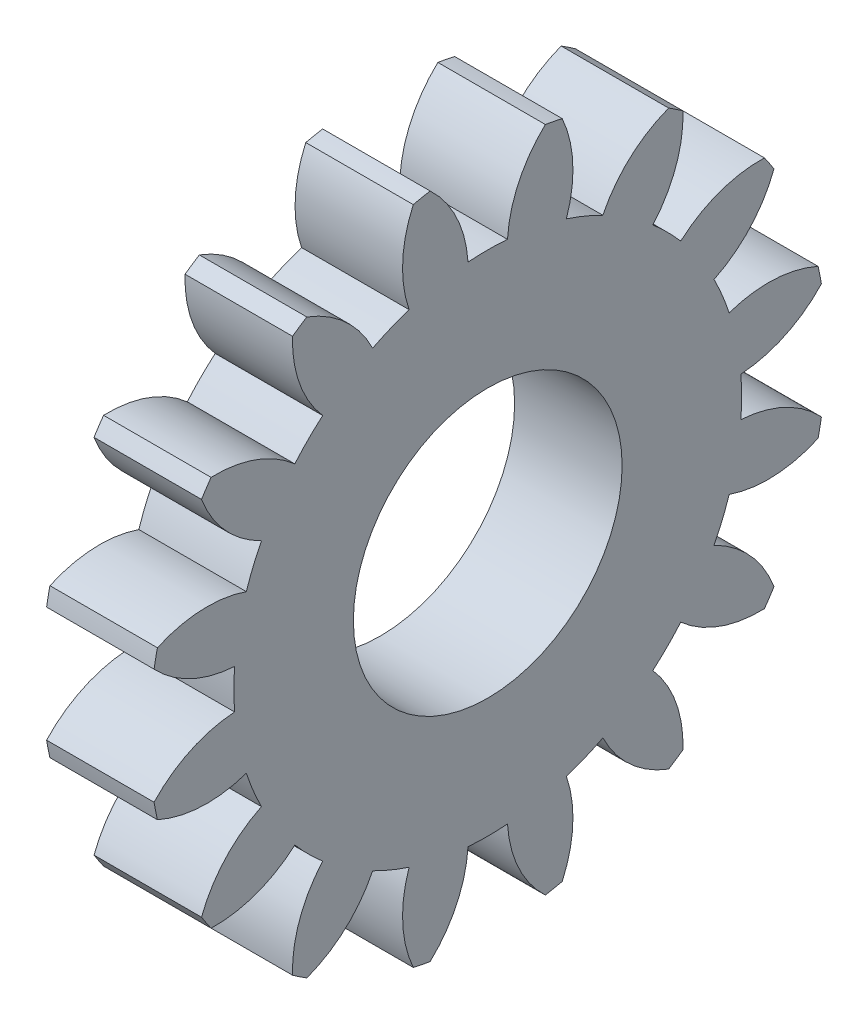
SolidWorks part; units mm, degrees
ref_plane "Plane1" through (0, 0, 0) normal (0, 0, 1) x (1, 0, 0)
ref_plane "Plane2" through (0, 0, 0) normal (0, 1, 0) x (1, 0, 0)
ref_plane "Plane3" through (0, 0, 0) normal (1, 0, 0) x (0, 0, -1)
sketch "HoldingSke" plane through (0, 0, 0) normal (0, 1, 0) x (1, 0, 0)
  line L0 (0, 0) -> (1.3732, -0.3938)
  line L1 (-15, 0) -> (100, 0) construction
  line L2 (0, 0) -> (-2.1039, 2.3779)
  line L3 (0, 0) -> (-11.863, 4.5341)
  line L4 (0, 0) -> (8.3015, 2.3804)
  line L5 (0, 0) -> (-46.8476, -17.4728)
  line L6 (0, 0) -> (-1.6579, -1.1186)
  line L7 (-2.1039, 2.3779) -> (8.6586, 51.2059)
  line L8 (-76.2, 54.61) -> (-75.3, 54.61)
  line L9 (-71.009, 38.7566) -> (-53.1078, 45.2721)
  line L10 (-76.2, 71.12) -> (104.1128, 71.12)
  line L11 (0, 0) -> (-2, 0)
  line L12 (-76.2, 101.6) -> (-76.173, 101.6)
  line L13 (24.9733, 27.94) -> (52.9518, 28.4284)
  line L14 (24.9733, 27.94) -> (24.9743, 27.94)
  line L15 (24.9733, 27.94) -> (100.4006, 29.5858)
  line L16 (-63.627, -0.7) -> (-12.827, -0.7)
  circle A0 centre (0, 0) radius 2.5
  circle A1 centre (0, 0) radius 4.724
  circle A2 centre (0, 0) radius 37.5
  circle A3 centre (0, 0) radius 2.5
  dimension "Hub_dia" = 75
  dimension "Overall_len" = 50
  dimension "OAL" = 50.0001
  dimension "Ap" = 20
  dimension "H" = 19.05
  dimension "Pitch_radius" = 180.3128
  dimension "Addendum_fac" = 1
  dimension "Dedendum_fac" = 1.25
  dimension "Clearance_fac" = 0.25
  dimension "Dedendum_add" = 0.001
sketch "BasProSke" plane through (0, 0, 0) normal (0, 1, 0) x (1, 0, 0)
  line L0 (-10, 0) -> (60, 0) construction
  line L1 (0, 0) -> (0, 6.3)
  line L2 (0, 0) -> (2, 0)
  line L3 (2, 0) -> (2, 6.3)
  line L4 (2, 6.3) -> (0, 6.3)
revolve "Base-Revolve" add sketch "BasProSke" angle 360 about L0
sketch "TooCutSke" plane through (0, 0, 0) normal (1, 0, 0) x (0, 0, -1)
  line L1 (0, 0) -> (0, 107) construction
  line L2 (0, 0) -> (-0.5961, 5.5682) construction
  line L3 (0, 0) -> (-2.1762, 10.9406) construction
  line L4 (-0.5961, 5.5682) -> (-1.0881, 5.4703) construction
  arc A0 (0.3672, 4.7097) -> (-0.3672, 4.7097) centre (0, 0) ccw
  arc A1 (1.0952, 6.2299) -> (-1.0952, 6.2299) centre (0, 0) ccw
  circle A2 centre (0, 0) radius 5.6 construction
  circle A3 centre (0, 0) radius 5.2623 construction
  arc A4 (-0.3672, 4.7097) -> (-1.0952, 6.2299) centre (-2.6031, 4.5734) ccw
  arc A5 (1.0952, 6.2299) -> (0.3672, 4.7097) centre (2.6031, 4.5734) ccw
extrude "ToothCut" cut sketch "TooCutSke" along normal through all
fillet "Breaks" [suppressed] radius 0.014
fillet "RootFillets" [suppressed] radius 0.176
pattern_circular "TeethCuts" count 16 every 22.5 about axis through (-10, 0, 0) along (1, 0, 0) of "ToothCut", "RootFillets", "Breaks"
sketch "HubNeaOneSke" plane through (0, 0, 0) normal (-1, 0, 0) x (0, 0, 1)
  circle A0 centre (0, 0) radius 4.724
extrude "HubNearOne" [suppressed] add sketch "HubNeaOneSke" along normal blind 48.0001
sketch "HubNeaBotSke" plane through (0, 0, 0) normal (-1, 0, 0) x (0, 0, 1)
  circle A0 centre (0, 0) radius 4.724
extrude "HubNearBoth" [suppressed] add sketch "HubNeaBotSke" along normal blind 24
ref_plane "FarPln" through (2, 0, 0) normal (1, 0, 0) x (0, 0, -1)
sketch "HubFarSke" plane through (2, 0, 0) normal (1, 0, 0) x (0, 0, -1)
  circle A0 centre (0, 0) radius 4.724
extrude "HubFar" [suppressed] add sketch "HubFarSke" along normal blind 24
sketch "BorSke" plane through (0, 0, 0) normal (1, 0, 0) x (0, 0, -1)
  circle A0 centre (0, 0) radius 2.5
extrude "Bore" cut sketch "BorSke" along normal mid plane 100.0001
sketch "KeySke" plane through (0, 0, 0) normal (1, 0, 0) x (0, 0, -1)
  line L0 (-1, 0) -> (-1, 3.4)
  line L1 (-1, 3.4) -> (1, 3.4)
  line L2 (1, 3.4) -> (1, 0)
  line L3 (0, 0) -> (0, 34) construction
  line L4 (-1, 0) -> (1, 0)
extrude "Keyway" [suppressed] cut sketch "KeySke" along normal mid plane 100.0001
pattern_circular "Keyway2" [suppressed] count 2 every 90 about axis through (-10, 0, 0) along (1, 0, 0)
equation "' \"Module@HoldingSke\" = 6.35"
equation "' \"Num_teeth@HoldingSke\" = 12"
equation "' \"Ap@HoldingSke\" =  20"
equation "' \"Ap@HoldingSke\" = 20"
equation "' \"Width@HoldingSke\" = 0.5 * 25.4"
equation "' \"Hub_dia@HoldingSke\"= 1 * 25.4"
equation "' \"Hub_dia@HoldingSke\" = 1 * 25.4"
equation "' \"Overall_len@HoldingSke\" = 1.0 * 25.4"
equation "' \"Bore@HoldingSke\" = 0.75 * 25.4"
equation "' \"T_dim@HoldingSke\" = 0.1 * 25.4"
equation "' \"Width@KeySke\" = 0.25 * 25.4"
equation "' \"Show_teeth@HoldingSke\" = 13"
equation "' \"Backlash@HoldingSke\" = 0.009 * 25.4"
equation "' \"Addendum_fac@HoldingSke\" = 1.0"
equation "' \"Dedendum_fac@HoldingSke\" = 1.25"
equation "' \"Dedendum_add@HoldingSke\" = 0.00005 * 25.4"
equation "' \"Clearance_fac@HoldingSke\" = 0.25"
equation "\"Pitch@HoldingSke\" = 1 / \"Module@HoldingSke\""
equation "\"Overcut_dia@TooCutSke\" = (\"Num_teeth@HoldingSke\" + 2 * \"Addendum_fac@HoldingSke\") / \"Pitch@HoldingSke\" + 0.002 * 25.4"
equation "\"Pitch_dia@TooCutSke\" = \"Num_teeth@HoldingSke\" / \"Pitch@HoldingSke\""
equation "\"Base_dia@TooCutSke\" = \"Num_teeth@HoldingSke\" / \"Pitch@HoldingSke\" * cos((\"Ap@HoldingSke\"  * 3.14159265 / 180))"
equation "\"Root_dia@TooCutSke\" = (\"Num_teeth@HoldingSke\" + 2) / \"Pitch@HoldingSke\" - 2 * (\"Addendum_fac@HoldingSke\" + \"Dedendum_fac@HoldingSke\") / \"Pitch@HoldingSke\" - \"Dedendum_add@HoldingSke\" * 2"
equation "\"Half_ang@TooCutSke\" = 180 / \"Num_teeth@HoldingSke\""
equation "\"Half_CT@TooCutSke\" = \"Num_teeth@HoldingSke\" / \"Pitch@HoldingSke\" * sin((3.14159265 / 2 / \"Num_teeth@HoldingSke\")) / 2 - 7 * \"Backlash@HoldingSke\" / 4"
equation "\"Flank_rad@TooCutSke\" = \"Num_teeth@HoldingSke\" / \"Pitch@HoldingSke\" / 5"
equation "\"Radius@RootFillets\" = \"Clearance_fac@HoldingSke\" / \"Pitch@HoldingSke\" + \"Dedendum_add@HoldingSke\""
equation "\"Break_rad@Breaks\" = 0.02 / \"Pitch@HoldingSke\""
equation "\"Thickness@HoldingSke\" = \"Width@HoldingSke\""
equation "\"OAL@HoldingSke\" = \"Thickness@HoldingSke\""
equation "\"MHD@HoldingSke\" = (\"Num_teeth@HoldingSke\" + 2) / \"Pitch@HoldingSke\" - 2 * (\"Addendum_fac@HoldingSke\" + \"Dedendum_fac@HoldingSke\")  / \"Pitch@HoldingSke\" - \"Dedendum_add@HoldingSke\" * 2"
equation "\"MBD@HoldingSke\" = (\"Num_teeth@HoldingSke\" + 2) / \"Pitch@HoldingSke\" - 2 * (\"Addendum_fac@HoldingSke\" + \"Dedendum_fac@HoldingSke\")  / \"Pitch@HoldingSke\" - \"Dedendum_add@HoldingSke\" * 2 - 0.002 * 25.4"
equation "\"MHD@HoldingSke\" = ((sgn( \"MHD@HoldingSke\" - \"Hub_dia@HoldingSke\" )-1)*( \"MHD@HoldingSke\" - \"Hub_dia@HoldingSke\" ))/-2+ \"Hub_dia@HoldingSke\""
equation "\"MBD@HoldingSke\" = ((sgn( \"MBD@HoldingSke\" - \"Bore@HoldingSke\" )-1)*( \"MBD@HoldingSke\" - \"Bore@HoldingSke\" ))/-2+ \"Bore@HoldingSke\""
equation "\"OAL@HoldingSke\" = ((sgn( \"OAL@HoldingSke\" - \"Overall_len@HoldingSke\" )+1)*( \"OAL@HoldingSke\" - \"Overall_len@HoldingSke\" ))/2 + \"Overall_len@HoldingSke\" + 0.000002 * 25.4"
equation "\"Num_teeth@TeethCuts\" = int( \"Show_teeth@HoldingSke\" ) + 1"
equation "\"Num_teeth@TeethCuts\" = ((sgn( \"Num_teeth@TeethCuts\" - \"Num_teeth@HoldingSke\" )-1)*( \"Num_teeth@TeethCuts\" - \"Num_teeth@HoldingSke\" ))/-2+ \"Num_teeth@HoldingSke\""
equation "\"Num_teeth@TeethCuts\" = ((sgn( \"Num_teeth@TeethCuts\" - 2.0)+1)*( \"Num_teeth@TeethCuts\" - 2.0))/2 +2.0"
equation "\"Angle@TeethCuts\" = 360.0 / \"Num_teeth@HoldingSke\""
equation "\"Diameter@BasProSke\" = (\"Num_teeth@HoldingSke\" + 2 * \"Addendum_fac@HoldingSke\") / \"Pitch@HoldingSke\""
equation "\"Thickness@BasProSke\"  = \"Thickness@HoldingSke\""
equation "' \"Fillet_rad@BasProSke\" =  \"Thickness@HoldingSke\" * 0.05"
equation "' \"Fillet_rad@BasProSke\" = \"Thickness@HoldingSke\" * 0.05"
equation "\"MHD@HoldingSke\" = ((sgn( \"MHD@HoldingSke\" - \"Root_dia@TooCutSke\" )-1)*( \"MHD@HoldingSke\" - \"Root_dia@TooCutSke\" ))/-2+ \"Root_dia@TooCutSke\""
equation "\"Diameter@HubNeaOneSke\" = \"MHD@HoldingSke\""
equation "\"Length@HubNearOne\" = \"OAL@HoldingSke\" - \"Thickness@BasProSke\""
equation "\"Diameter@HubNeaBotSke\" = \"MHD@HoldingSke\""
equation "\"Length@HubNearBoth\" = ( \"OAL@HoldingSke\" - \"Thickness@BasProSke\" ) / 2.0"
equation "\"Thickness@FarPln\" = \"Thickness@BasProSke\""
equation "\"Diameter@HubFarSke\" = \"MHD@HoldingSke\""
equation "\"Length@HubFar\" = ( \"OAL@HoldingSke\" - \"Thickness@BasProSke\" ) / 2.0"
equation "\"Diameter@BorSke\" = \"MBD@HoldingSke\""
equation "\"D1@Bore\" = \"OAL@HoldingSke\" * 2.0"
equation "\"D1@Keyway\" = \"OAL@HoldingSke\" * 2.0"
equation "\"Offset@KeySke\" = \"T_dim@HoldingSke\" + \"MBD@HoldingSke\" / 2.0"
